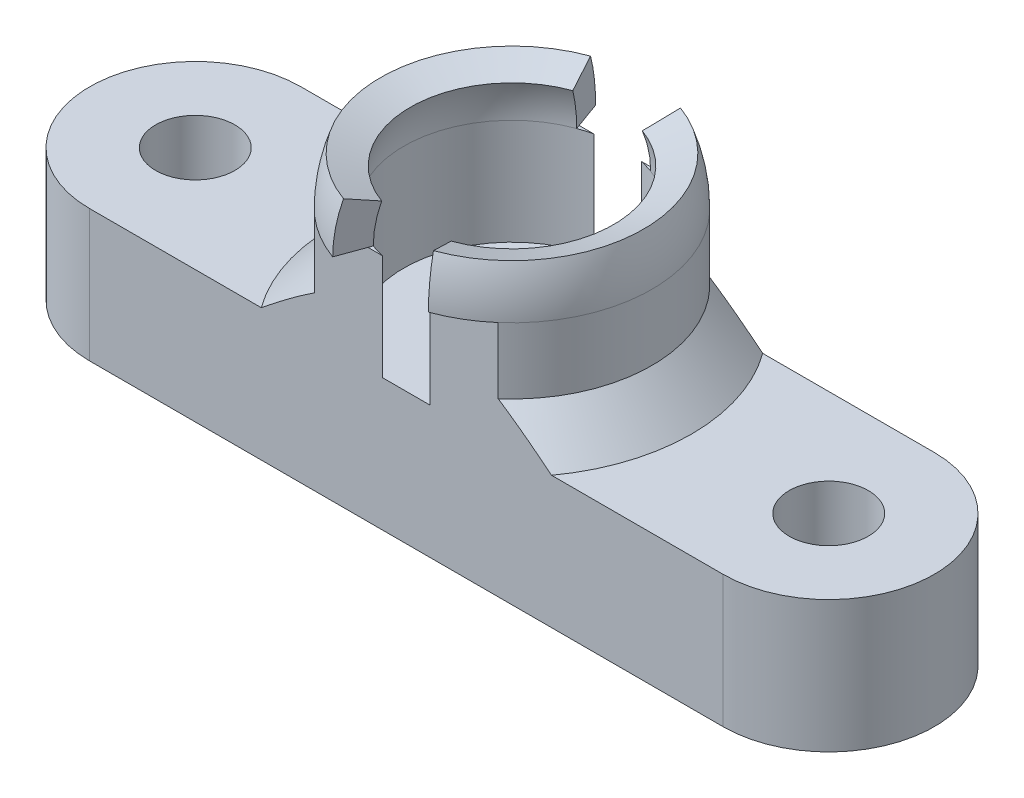
SolidWorks part; units mm, degrees
ref_plane "Alzado" through (0, 0, 0) normal (0, 0, 1) x (1, 0, 0)
ref_plane "Planta" through (0, 0, 0) normal (0, 1, 0) x (1, 0, 0)
ref_plane "Vista lateral" through (0, 0, 0) normal (1, 0, 0) x (0, 0, -1)
sketch "Croquis1" plane through (0, 0, 0) normal (0, 1, 0) x (1, 0, 0)
  line L0 (-12, 0) -> (12, 0)
  line L1 (-12, 4) -> (12, 4)
  line L2 (12, -4) -> (-12, -4)
  circle A0 centre (12, 0) radius 1.5
  circle A1 centre (-12, 0) radius 1.5
  arc A2 (-12, -4) -> (-12, 4) centre (-12, 0) cw
  arc A3 (12, 4) -> (12, -4) centre (12, 0) cw
  point P4 (0, 0)
  dimension "D2" = 3
  dimension "D3" = 3
  dimension "D4" = 4
  dimension "D5" = 4
  dimension "D1" = 24
extrude "Saliente-Extruir1" add sketch "Croquis1" along normal blind 5
sketch "Croquis2" plane through (0, 5, 0) normal (0, 1, 0) x (1, 0, 0)
  line L0 (-12, 4) -> (12, 4) construction
  line L1 (12, -4) -> (-12, -4) construction
  line L2 (12, -4) -> (-12, -4)
  line L3 (-12, 4) -> (12, 4)
  arc A0 (-0.9, 4) -> (-0.9, -4) centre (0, 0) ccw
  arc A1 (0.9, 4) -> (0.9, -4) centre (0, 0) cw
  arc A2 (-3.4771, 4) -> (-3.4771, -4) centre (0, 0) ccw
  arc A3 (3.4771, 4) -> (3.4771, -4) centre (0, 0) cw
  line M5 (-12, -4) -> (12, -4)
  dimension "D1" = 4.1
  dimension "D2" = 4.1
  dimension "D3" = 5.3
  dimension "D4" = 5.3
extrude "Saliente-Extruir2" add sketch "Croquis2" along normal blind 4 contours L3 A2 L2 A0 | A3 L3 A1 M5
sketch "Croquis4" plane through (0, 0, 0) normal (0, 0, 1) x (1, 0, 0)
  line L0 (-3.4771, 9) -> (-0.9, 9) construction
  line L1 (-0.9, 9) -> (-4.1, 9) construction
  line L2 (-5.3, 9) -> (-5.3, 5) construction
  line L3 (-3.4771, 9) -> (-5.3, 9) construction
  line L4 (-3.4771, 9) -> (-0.9, 9)
  line L5 (-0.9, 9) -> (-4.1, 9)
  line L6 (-5.3, 9) -> (-5.3, 5)
  line L7 (-3.4771, 9) -> (-5.3, 9)
  line L8 (-4.9804, 10.8127) -> (-3.8527, 10.4023)
  line L9 (3.8527, 10.4023) -> (4.9804, 10.8127)
  line L10 (-5.3, 9) -> (-4.1, 9)
  line L11 (4.1, 9) -> (5.3, 9)
  line L12 (0, 9) -> (0, 9.943) construction
  arc A0 (-4.1, 9) -> (-3.8527, 10.4023) centre (0, 9) cw
  arc A1 (-5.3, 9) -> (-4.9804, 10.8127) centre (0, 9) cw
  arc A2 (4.1, 9) -> (3.8527, 10.4023) centre (0, 9) ccw
  arc A3 (5.3, 9) -> (4.9804, 10.8127) centre (0, 9) ccw
revolve "Revolución1" add sketch "Croquis4" angle 70 about L12 other way angle 70
sketch "Croquis5" plane through (0, 0, 0) normal (0, 0, 1) x (1, 0, 0)
  line L0 (-5.3, 9) -> (-5.3, 5) construction
  line L1 (-0.9, 9) -> (-4.1, 9) construction
  line L2 (-3.4771, 9) -> (-0.9, 9) construction
  line L3 (-3.4771, 9) -> (-5.3, 9) construction
  line L4 (-5.3, 9) -> (-4.1, 9) construction
  line L5 (-4.9804, 10.8127) -> (-3.8527, 10.4023) construction
  line L6 (3.8527, 10.4023) -> (4.9804, 10.8127) construction
  line L7 (4.1, 9) -> (5.3, 9) construction
  line L8 (-5.3, 9) -> (-5.3, 5)
  line L9 (-0.9, 9) -> (-4.1, 9)
  line L10 (-3.4771, 9) -> (-0.9, 9)
  line L11 (-3.4771, 9) -> (-5.3, 9)
  line L12 (-5.3, 9) -> (-4.1, 9)
  line L13 (-4.9804, 10.8127) -> (-3.8527, 10.4023)
  line L14 (3.8527, 10.4023) -> (4.9804, 10.8127)
  line L15 (4.1, 9) -> (5.3, 9)
  line L16 (0, 9) -> (0, 10.8712) construction
  arc A0 (-3.8527, 10.4023) -> (-4.1, 9) centre (0, 9) ccw construction
  arc A1 (-4.9804, 10.8127) -> (-5.3, 9) centre (0, 9) ccw construction
  arc A2 (5.3, 9) -> (4.9804, 10.8127) centre (0, 9) ccw construction
  arc A3 (4.1, 9) -> (3.8527, 10.4023) centre (0, 9) ccw construction
  arc A4 (-3.8527, 10.4023) -> (-4.1, 9) centre (0, 9) ccw
  arc A5 (-4.9804, 10.8127) -> (-5.3, 9) centre (0, 9) ccw
  arc A6 (5.3, 9) -> (4.9804, 10.8127) centre (0, 9) ccw
  arc A7 (4.1, 9) -> (3.8527, 10.4023) centre (0, 9) ccw
revolve "Revolución2" add sketch "Croquis5" angle 70 about L16 other way angle 70
chamfer "Chaflán1" distance 1.5 angle 45 2 edges at (-5.3, 5, 0) (5.3, 5, 0)
